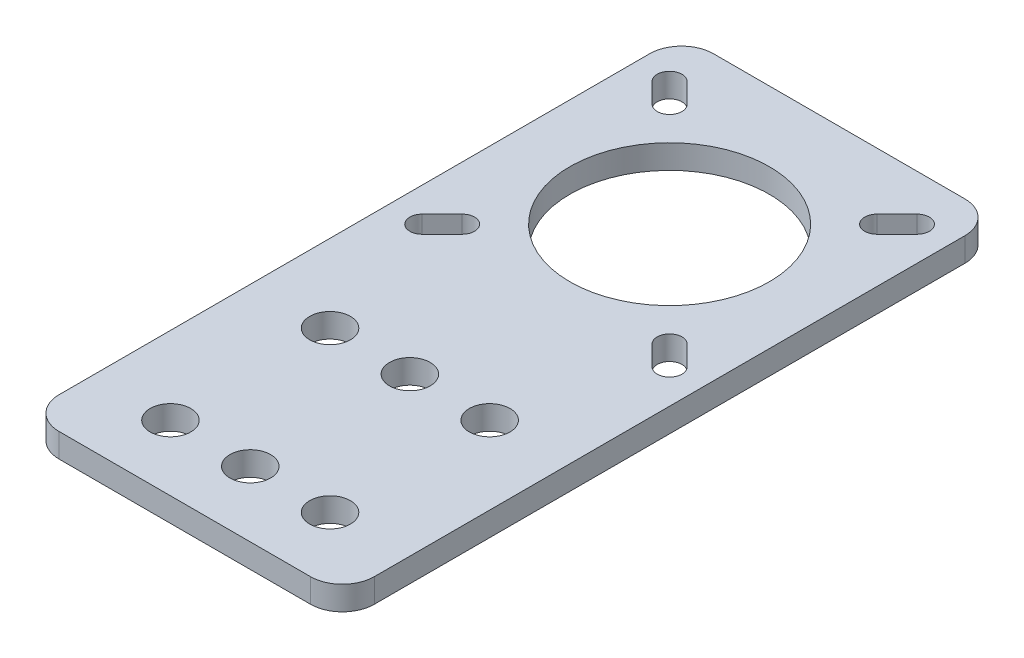
SolidWorks part; units mm, degrees
ref_plane "Front Plane" through (0, 0, 0) normal (0, 0, 1) x (1, 0, 0)
ref_plane "Top Plane" through (0, 0, 0) normal (0, 1, 0) x (1, 0, 0)
ref_plane "Right Plane" through (0, 0, 0) normal (1, 0, 0) x (0, 0, -1)
sketch "Sketch1" plane through (0, 0, 0) normal (0, 1, 0) x (1, 0, 0)
  line L1 (-19.75, -41) -> (19.75, -41)
  line L2 (-19.75, -41) -> (-19.75, 41)
  line L3 (-19.75, 41) -> (19.75, 41)
  line L4 (19.75, -41) -> (19.75, 41)
  line L5 (-19.75, -41) -> (19.75, 41) construction
  line L6 (-19.75, 41) -> (19.75, -41) construction
  point P0 (0, 0)
  dimension "D1" = 82
  dimension "D2" = 39.5
extrude "Boss-Extrude1" add sketch "Sketch1" along normal blind 3
sketch "Sketch2" plane through (0, 3, 0) normal (0, 1, 0) x (1, 0, 0)
  line L0 (0, 41) -> (0, -41) construction
  line L1 (19.75, 41) -> (-19.75, 41) construction
  line L2 (-19.75, -41) -> (19.75, -41) construction
  line L3 (-19.75, -32.8) -> (19.75, -32.8) construction
  line L4 (-19.75, 41) -> (-19.75, -41) construction
  line L5 (19.75, -41) -> (19.75, 41) construction
  line L6 (-19.75, -12.8) -> (19.75, -12.8) construction
  line L7 (-19.75, 0) -> (19.75, 0) construction
  line L8 (-15.5, 41) -> (-15.5, 0) construction
  line L9 (-13, 41) -> (-13, 0) construction
  line L10 (-15.5, 4.25) -> (-13, 6.75)
  line L11 (-13, 6.75) -> (-14.096, 7.846)
  line L12 (-13, 6.75) -> (-11.904, 5.654)
  line L13 (-15.5, 4.25) -> (-14.404, 3.154)
  line L14 (-15.5, 4.25) -> (-16.596, 5.346)
  line L15 (-16.596, 5.346) -> (-14.096, 7.846)
  line L16 (-14.404, 3.154) -> (-11.904, 5.654)
  line L17 (-13, 32.75) -> (-11.904, 33.846)
  line L18 (-13, 32.75) -> (-14.096, 31.654)
  line L19 (-15.5, 35.25) -> (-16.596, 34.154)
  line L20 (-15.5, 35.25) -> (-14.404, 36.346)
  line L21 (-16.596, 34.154) -> (-14.096, 31.654)
  line L22 (-14.404, 36.346) -> (-11.904, 33.846)
  line L23 (15.5, 35.25) -> (14.404, 36.346)
  line L24 (15.5, 35.25) -> (16.596, 34.154)
  line L25 (16.596, 34.154) -> (14.096, 31.654)
  line L26 (13, 32.75) -> (14.096, 31.654)
  line L27 (13, 32.75) -> (11.904, 33.846)
  line L28 (14.404, 36.346) -> (11.904, 33.846)
  line L29 (16.596, 5.346) -> (14.096, 7.846)
  line L30 (14.404, 3.154) -> (11.904, 5.654)
  circle A0 centre (0, 19.75) radius 12.5
  circle A1 centre (0, -32.8) radius 2.55
  circle A2 centre (0, -12.8) radius 2.55
  circle A3 centre (-10, -12.8) radius 2.55
  circle A4 centre (-10, -32.8) radius 2.55
  circle A5 centre (10, -32.8) radius 2.55
  circle A6 centre (10, -12.8) radius 2.55
  circle A8 centre (-15.5, 35.25) radius 1.55
  circle A9 centre (-13, 32.75) radius 1.55
  circle A10 centre (-15.5, 4.25) radius 1.55
  circle A11 centre (-13, 6.75) radius 1.55
  circle A12 centre (13, 32.75) radius 1.55
  circle A13 centre (15.5, 35.25) radius 1.55
  circle A14 centre (13, 6.75) radius 1.55
  circle A15 centre (15.5, 4.25) radius 1.55
  dimension "D3" = 21.25
  dimension "D4" = 25
  dimension "D5" = 5.1
  dimension "D6" = 5.1
  dimension "D7" = 9.75
  dimension "D8" = 5.1
  dimension "D9" = 9.75
  dimension "D10" = 5.1
  dimension "D13" = 5.75
  dimension "D14" = 8.25
  dimension "D15" = 3.1
  dimension "D16" = 3.1
  dimension "D17" = 36.75
  dimension "D18" = 34.25
  dimension "D19" = 3.1
  dimension "D20" = 3.1
  dimension "D1" = 73.8
  dimension "D2" = 53.8
  dimension "D11" = 4.25
  dimension "D12" = 6.75
  dimension "D21" = 45
  dimension "D22" = 45
  dimension "D23" = 45
  dimension "D24" = 45
extrude "Cut-Extrude1" cut sketch "Sketch2" against normal through all contours A0 | L20 A8 L19 | L19 A8 L20 | A9 L22 A8 L21 | L17 A9 L18 | L18 A9 L17 | L11 A11 L10 | A11 L15 A10 L10 | L12 A11 L11 | L10 A11 L12 | A11 L10 A10 L16 | L13 A10 L10 | L10 A10 L14 | L14 A10 L13 | A14 | L30 A15 L29 A14 | A15 | A12 L26 L27 | A13 L23 L24 | A3 | A2 | A6 | A4 | A1 | A5
fillet "Fillet1" radius 4 4 edges at (-19.75, 1.5, 41) (19.75, 1.5, 41) (-19.75, 1.5, -41) (19.75, 1.5, -41)
